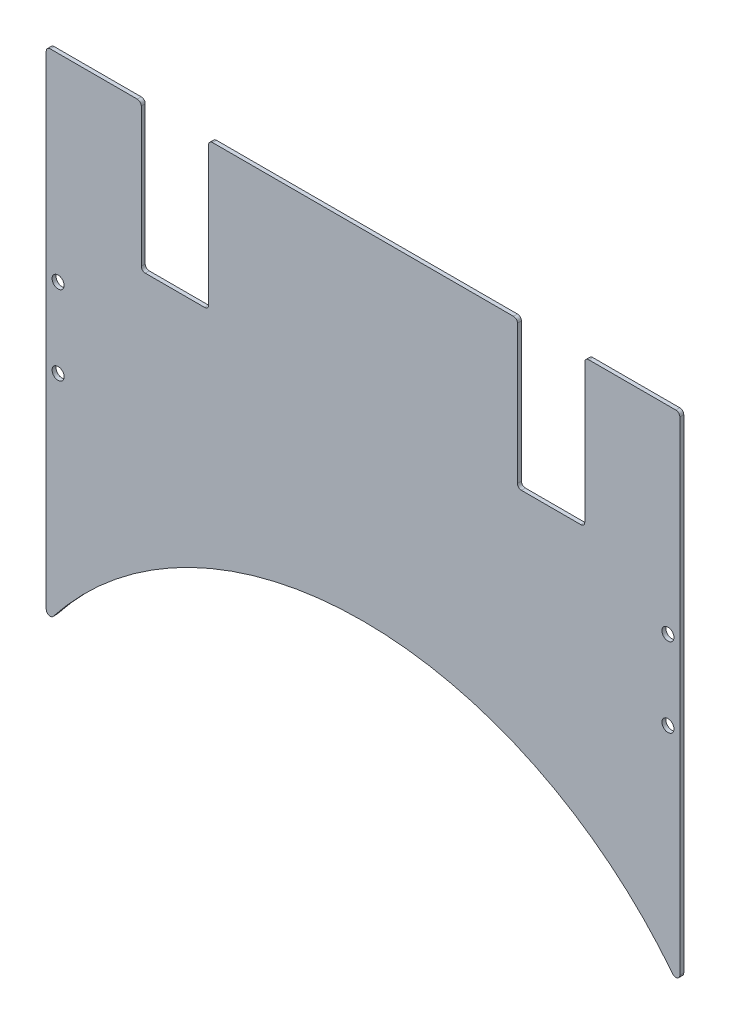
SolidWorks part; units mm, degrees
material "Thornel Mat VMA"
ref_plane "前视基准面" through (0, 0, 0) normal (0, 0, 1) x (1, 0, 0)
ref_plane "上视基准面" through (0, 0, 0) normal (0, 1, 0) x (1, 0, 0)
ref_plane "右视基准面" through (0, 0, 0) normal (1, 0, 0) x (0, 0, -1)
other "Configuration Table"
sketch "草图1" plane through (0, 0, 0) normal (0, 0, 1) x (1, 0, 0)
  line L1 (-80, -52) -> (80, -52)
  line L2 (-80, -52) -> (-80, 52)
  line L3 (-80, 52) -> (80, 52)
  line L4 (80, -52) -> (80, 52)
  line L5 (-80, -52) -> (80, 52) construction
  line L6 (-80, 52) -> (80, -52) construction
  point P0 (0, 0)
  dimension "D1" = 160
  dimension "D2" = 104
extrude "凸台-拉伸1" add sketch "草图1" along normal mid plane 1
sketch "草图2" [suppressed] plane through (0, 0, -0.5) normal (0, 0, -1) x (-1, 0, 0)
  line L0 (-135.1912, -16.9365) -> (135.1912, -16.9365) construction
  line L1 (-135.1912, -16.9365) -> (135.1912, -16.9365) construction
  line L2 (-80, -52) -> (-80, 52) construction
  line L3 (-80, -18.9365) -> (80, -18.9365)
  line L4 (-80, -18.9365) -> (-80, 52)
  line L5 (-80, 52) -> (80, 52)
  line L6 (80, -18.9365) -> (80, 52)
  dimension "D1" = 2
extrude "切除-拉伸1" [suppressed] cut sketch "草图2" against normal mid plane 3
sketch "草图3" [suppressed] plane through (0, 0, -0.5) normal (0, 0, -1) x (-1, 0, 0)
  line L0 (80, 52) -> (80, -52) construction
  line L1 (-80, -52) -> (80, -52)
  line L2 (-80, -52) -> (-80, 12)
  line L3 (-80, 12) -> (80, 12)
  line L4 (80, -52) -> (80, 12)
  line L5 (-80, 52) -> (80, 52) construction
  dimension "D1" = 40
extrude "切除-拉伸2" [suppressed] cut sketch "草图3" against normal mid plane 11
sketch "草图4" [suppressed] plane through (0, 0, -0.5) normal (0, 0, -1) x (-1, 0, 0)
  line L0 (80, 12) -> (-80, 12) construction
  line L1 (-65, 4) -> (65, 4)
  line L2 (-65, 4) -> (-65, 20)
  line L3 (-65, 20) -> (65, 20)
  line L4 (65, 4) -> (65, 20)
  line L5 (-65, 4) -> (65, 20) construction
  line L6 (-65, 20) -> (65, 4) construction
  line L7 (80, 52) -> (80, 12) construction
  point P0 (0, 12)
  dimension "D1" = 8
  dimension "D2" = 15
extrude "切除-拉伸3" [suppressed] cut sketch "草图4" against normal mid plane 11
sketch "草图7" [suppressed] plane through (0, 0, -0.5) normal (0, 0, -1) x (-1, 0, 0)
  line L5 (97.3576, 131.0846) -> (63.5, 131.0846)
  line L6 (63.5, 131.0846) -> (63.5, 72.0846)
  line L7 (63.5, 72.0846) -> (-63.5, 72.0846)
  line L8 (-63.5, 72.0846) -> (-63.5, 82.0846)
  line L9 (-63.5, 82.0846) -> (-83.5434, 82.0846)
  line L10 (97.3576, 131.0846) -> (63.5, 131.0846)
  line L11 (63.5, 131.0846) -> (63.5, 72.0846)
  line L12 (63.5, 72.0846) -> (-63.5, 72.0846)
  line L13 (-63.5, 72.0846) -> (-63.5, 82.0846)
  line L14 (-63.5, 82.0846) -> (-83.5434, 82.0846)
  arc A1 (-83.5434, 82.0846) -> (97.3576, 131.0846) centre (0, 132.0846) ccw
  arc A2 (-83.5434, 82.0846) -> (97.3576, 131.0846) centre (0, 132.0846) ccw
  dimension "D1" = 0
sketch "草图8" [suppressed] plane through (0, 0, -0.5) normal (0, 0, -1) x (-1, 0, 0)
  line L5 (63.5, 133.0846) -> (97.3576, 133.0846)
  line L6 (-92.6256, 162.0846) -> (-63.5, 162.0846)
  line L7 (-63.5, 162.0846) -> (-63.5, 192.0846)
  line L8 (-63.5, 192.0846) -> (63.5, 192.0846)
  line L9 (63.5, 192.0846) -> (63.5, 133.0846)
  line L10 (63.5, 133.0846) -> (97.3576, 133.0846)
  line L11 (-92.6256, 162.0846) -> (-63.5, 162.0846)
  line L12 (-63.5, 162.0846) -> (-63.5, 192.0846)
  line L13 (-63.5, 192.0846) -> (63.5, 192.0846)
  line L14 (63.5, 192.0846) -> (63.5, 133.0846)
  arc A1 (97.3576, 133.0846) -> (-92.6256, 162.0846) centre (0, 132.0846) ccw
  arc A2 (97.3576, 133.0846) -> (-92.6256, 162.0846) centre (0, 132.0846) ccw
  dimension "D1" = 0
sketch "草图9" [suppressed] plane through (0, 0, -0.5) normal (0, 0, -1) x (-1, 0, 0)
  line L5 (-64.5, -134) -> (-96.342, -134)
  line L6 (73.5, -163) -> (64.5, -163)
  line L7 (63.5, -164) -> (63.5, -190)
  line L8 (60.5, -193) -> (-60.5, -193)
  line L17 (-63.5, -190) -> (-63.5, -135)
  line L19 (95.3403, -118) -> (84.5, -118)
  line L21 (83.5, -119) -> (83.5, -153)
  circle A0 centre (0, -133) radius 99.3627
  arc A1 (64.5, -163) -> (63.5, -164) centre (64.5, -164) ccw
  arc A13 (60.5, -193) -> (63.5, -190) centre (60.5, -190) ccw
  arc A15 (-63.5, -190) -> (-60.5, -193) centre (-60.5, -190) ccw
  arc A17 (-63.5, -135) -> (-64.5, -134) centre (-64.5, -135) ccw
  arc A19 (-96.342, -134) -> (-97.3418, -135.0208) centre (-96.342, -135) ccw
  arc A21 (-97.3418, -135.0208) -> (96.3297, -118.8547) centre (0, -133) ccw
  arc A22 (-97.3418, -135.0208) -> (96.3297, -118.8547) centre (0, -133) ccw construction
  arc A23 (96.3297, -118.8547) -> (95.3403, -118) centre (95.3403, -119) ccw
  arc A25 (84.5, -118) -> (83.5, -119) centre (84.5, -119) ccw
  arc A27 (73.5, -163) -> (83.5, -153) centre (73.5, -153) ccw
  dimension "D2" = 2
  dimension "D1" = 0
extrude "切除-拉伸4" [suppressed] cut sketch "草图9" against normal mid plane 31
sketch "草图10" [suppressed] plane through (0, 0, -0.5) normal (0, 0, -1) x (-1, 0, 0)
  line L0 (-80, -52) -> (-80, -74.0682)
  line L1 (-80, -52) -> (-57.5496, -52)
  arc A0 (-57.5496, -52) -> (-80, -74.0682) centre (0, -133) ccw
  arc A1 (57.5496, -52) -> (-57.5496, -52) centre (0, -133) ccw construction
extrude "凸台-拉伸2" [suppressed] add sketch "草图10" against normal up to surface (1 mm away)
mirror "镜向1" [suppressed] about plane through (0, 0, 0) normal (1, 0, 0)
sketch "草图11" [suppressed] plane through (0, 0, -0.5) normal (0, 0, -1) x (-1, 0, 0)
  line L5 (-1, 35.7426) -> (-1, 67.5846)
  line L6 (-2, 68.5846) -> (-57, 68.5846)
  line L7 (-60, 71.5846) -> (-60, 192.5846)
  line L9 (-50, 196.5846) -> (-50, 213.8451)
  line L15 (-57, 195.5846) -> (-51, 195.5846)
  circle A0 centre (0, 132.0846) radius 99.3627
  arc A1 (-51.5293, 214.6935) -> (-2.0208, 34.7428) centre (0, 132.0846) ccw
  arc A10 (-51.5293, 214.6935) -> (-2.0208, 34.7428) centre (0, 132.0846) ccw construction
  arc A11 (-2.0208, 34.7428) -> (-1, 35.7426) centre (-2, 35.7426) ccw
  arc A13 (-1, 67.5846) -> (-2, 68.5846) centre (-2, 67.5846) ccw
  arc A15 (-60, 71.5846) -> (-57, 68.5846) centre (-57, 71.5846) ccw
  arc A17 (-57, 195.5846) -> (-60, 192.5846) centre (-57, 192.5846) ccw
  arc A19 (-51, 195.5846) -> (-50, 196.5846) centre (-51, 196.5846) ccw
  arc A21 (-50, 213.8451) -> (-51.5293, 214.6935) centre (-51, 213.8451) ccw
  dimension "D2" = 2
  dimension "D1" = 0
extrude "切除-拉伸5" [suppressed] cut sketch "草图11" against normal up to surface (1 mm away)
sketch "草图12" plane through (0, 0, -0.5) normal (0, 0, -1) x (-1, 0, 0)
  line L5 (96.342, -134) -> (64.5, -134)
  line L6 (63.5, -135) -> (63.5, -190)
  line L7 (60.5, -193) -> (-60.5, -193)
  line L9 (-64.5, -183) -> (-81.7605, -183)
  line L20 (-63.5, -190) -> (-63.5, -184)
  circle A0 centre (0, -133) radius 99.3627
  arc A1 (-82.609, -184.5293) -> (97.3418, -135.0208) centre (0, -133) ccw
  arc A17 (-82.609, -184.5293) -> (97.3418, -135.0208) centre (0, -133) ccw construction
  arc A18 (97.3418, -135.0208) -> (96.342, -134) centre (96.342, -135) ccw
  arc A20 (64.5, -134) -> (63.5, -135) centre (64.5, -135) ccw
  arc A22 (60.5, -193) -> (63.5, -190) centre (60.5, -190) ccw
  arc A24 (-63.5, -190) -> (-60.5, -193) centre (-60.5, -190) ccw
  arc A26 (-63.5, -184) -> (-64.5, -183) centre (-64.5, -184) ccw
  arc A28 (-81.7605, -183) -> (-82.609, -184.5293) centre (-81.7605, -184) ccw
  dimension "D2" = 2
  dimension "D1" = 0
extrude "切除-拉伸6" cut sketch "草图12" against normal up to surface (1 mm away) up to face at (0, 0, 0.5)
sketch "草图13" plane through (0, 0, -0.5) normal (0, 0, -1) x (-1, 0, 0)
  line L0 (80, -52) -> (80, -74.0682)
  line L1 (80, -52) -> (57.5496, -52)
  arc A0 (80, -74.0682) -> (57.5496, -52) centre (0, -133) ccw
  arc A1 (57.5496, -52) -> (-57.5496, -52) centre (0, -133) ccw construction
extrude "凸台-拉伸3" add sketch "草图13" against normal up to surface (1 mm away) up to face at (0, -14.2729, 0.5)
mirror "镜向2" about plane through (0, 0, 0) normal (1, 0, 0) of "凸台-拉伸3"
sketch "草图14" [suppressed] plane through (0, 0, -0.5) normal (0, 0, -1) x (-1, 0, 0)
  line L5 (1, -196.5846) -> (1, -228.4266)
  line L6 (30, -58.5846) -> (30, -67.5846)
  line L7 (31, -68.5846) -> (57, -68.5846)
  line L8 (60, -71.5846) -> (60, -192.5846)
  line L17 (57, -195.5846) -> (2, -195.5846)
  line L19 (-15, -36.7442) -> (-15, -47.5846)
  line L21 (-14, -48.5846) -> (20, -48.5846)
  circle A0 centre (0, -132.0846) radius 99.3627
  arc A1 (30, -67.5846) -> (31, -68.5846) centre (31, -67.5846) ccw
  arc A13 (60, -71.5846) -> (57, -68.5846) centre (57, -71.5846) ccw
  arc A15 (57, -195.5846) -> (60, -192.5846) centre (57, -192.5846) ccw
  arc A17 (2, -195.5846) -> (1, -196.5846) centre (2, -196.5846) ccw
  arc A19 (1, -228.4266) -> (2.0208, -229.4263) centre (2, -228.4266) ccw
  arc A21 (2.0208, -229.4263) -> (-14.1453, -35.7548) centre (0, -132.0846) ccw
  arc A22 (2.0208, -229.4263) -> (-14.1453, -35.7548) centre (0, -132.0846) ccw construction
  arc A23 (-14.1453, -35.7548) -> (-15, -36.7442) centre (-14, -36.7442) ccw
  arc A25 (-15, -47.5846) -> (-14, -48.5846) centre (-14, -47.5846) ccw
  arc A27 (30, -58.5846) -> (20, -48.5846) centre (20, -58.5846) ccw
  dimension "D2" = 2
  dimension "D1" = 0
extrude "切除-拉伸7" [suppressed] cut sketch "草图14" against normal up to surface (1 mm away)
sketch "草图15" [suppressed] plane through (0, 0, -0.5) normal (0, 0, -1) x (-1, 0, 0)
  line L0 (-53.2393, -34.6238) -> (53.2393, -34.6238)
  line L2 (-53.2393, -34.6238) -> (-53.2393, 13.2547)
  line L3 (-53.2393, 13.2547) -> (53.2393, 13.2547)
  line L4 (-44.0576, -29.6238) -> (44.9575, -29.6238)
  line L5 (46.2393, -28.3422) -> (46.2393, 6.973)
  line L6 (44.9576, 8.2547) -> (-44.0575, 8.2547)
  line L7 (-45.3393, 6.973) -> (-45.3393, -28.3421)
  line L8 (-44.0576, -29.6238) -> (44.9575, -29.6238) construction
  line L9 (46.2393, -28.3422) -> (46.2393, 6.973) construction
  line L10 (44.9576, 8.2547) -> (-44.0575, 8.2547) construction
  line L11 (-45.3393, 6.973) -> (-45.3393, -28.3421) construction
  line L12 (53.2393, -34.6238) -> (53.2393, 13.2547)
  line L13 (-53.2393, -78.6983) -> (53.2393, 13.2547) construction
  line L14 (-53.2393, 13.2547) -> (53.2393, -78.6983) construction
  arc A0 (58.8168, -52) -> (-58.8168, -52) centre (0, -132.0846) ccw construction
  spline S4 degree 2 poles (-566.7757, 2906.9066) (4.2164, -46.3747) (45.447, -29.5283) (45.6842, -29.4314) (45.866, -29.2496) (46.047, -29.0686) (46.1444, -28.8297) (62.928, 12.3297) (-2890.172, 583.6967) knots -43.419559 -43.419559 -43.419559 0.25 0.25 0.5 0.5 0.75 0.75 44.517285 44.517285 44.517285 only from (44.9575, -29.6238) to (46.2393, -28.3422)
  spline S5 degree 2 poles (-2890.2912, -604.7603) (62.9901, -33.7681) (46.1437, 7.4624) (46.0468, 7.6996) (45.865, 7.8814) (45.684, 8.0624) (45.4451, 8.1599) (4.2857, 24.9435) (-567.0812, -2928.1565) knots -43.419559 -43.419559 -43.419559 0.25 0.25 0.5 0.5 0.75 0.75 44.517285 44.517285 44.517285 only from (46.2393, 6.973) to (44.9576, 8.2547)
  spline S6 degree 2 poles (567.6757, -2928.2758) (-3.3164, 25.0055) (-44.547, 8.1592) (-44.7842, 8.0622) (-44.966, 7.8804) (-45.147, 7.6995) (-45.2444, 7.4605) (-62.028, -33.6989) (2891.072, -605.0658) knots -43.419559 -43.419559 -43.419559 0.25 0.25 0.5 0.5 0.75 0.75 44.517285 44.517285 44.517285 only from (-44.0575, 8.2547) to (-45.3393, 6.973)
  spline S7 degree 2 poles (2891.1912, 583.3911) (-62.0901, 12.399) (-45.2437, -28.8315) (-45.1468, -29.0688) (-44.965, -29.2506) (-44.784, -29.4316) (-44.5451, -29.529) (-3.3857, -46.3126) (567.9812, 2906.7874) knots -43.419559 -43.419559 -43.419559 0.25 0.25 0.5 0.5 0.75 0.75 44.517285 44.517285 44.517285 only from (-45.3393, -28.3421) to (-44.0576, -29.6238)
  spline S8 degree 2 poles (44.9575, -29.6238) (45.2109, -29.6247) (45.447, -29.5283) (45.6842, -29.4314) (45.866, -29.2496) (46.047, -29.0686) (46.1444, -28.8297) (46.2403, -28.5946) (46.2393, -28.3422) knots 0 0 0 0.25 0.25 0.5 0.5 0.75 0.75 1 1 1 construction
  spline S9 degree 2 poles (46.2393, 6.973) (46.2402, 7.2264) (46.1437, 7.4624) (46.0468, 7.6996) (45.865, 7.8814) (45.684, 8.0624) (45.4451, 8.1599) (45.21, 8.2557) (44.9576, 8.2547) knots 0 0 0 0.25 0.25 0.5 0.5 0.75 0.75 1 1 1 construction
  spline S10 degree 2 poles (-44.0575, 8.2547) (-44.3109, 8.2556) (-44.547, 8.1592) (-44.7842, 8.0622) (-44.966, 7.8804) (-45.147, 7.6995) (-45.2444, 7.4605) (-45.3403, 7.2254) (-45.3393, 6.973) knots 0 0 0 0.25 0.25 0.5 0.5 0.75 0.75 1 1 1 construction
  spline S11 degree 2 poles (-45.3393, -28.3421) (-45.3402, -28.5955) (-45.2437, -28.8315) (-45.1468, -29.0688) (-44.965, -29.2506) (-44.784, -29.4316) (-44.5451, -29.529) (-44.31, -29.6249) (-44.0576, -29.6238) knots 0 0 0 0.25 0.25 0.5 0.5 0.75 0.75 1 1 1 construction
  point P2 (0, -32.7218)
  dimension "D2" = 5
  dimension "D3" = 7
  dimension "D4" = 98.373
  dimension "D5" = 5
  dimension "D1" = 0
sketch "草图16" [suppressed] plane through (0, 0, -0.5) normal (0, 0, -1) x (-1, 0, 0)
  line L0 (-50, 40.2284) -> (-50, 32.9426) construction
  line L1 (-50, 32.9426) -> (-45, 32.9426) construction
  line L2 (-45, 32.9426) -> (-45, 40.2284) construction
  line L3 (-45, 40.2284) -> (-40, 40.2284) construction
  line L4 (-40, 40.2284) -> (-40, 42.35) construction
  line L5 (-40, 42.35) -> (-55, 42.35) construction
  line L6 (-55, 42.35) -> (-55, 40.2284) construction
  line L7 (-55, 40.2284) -> (-50, 40.2284) construction
  line L8 (-43, 64.0846) -> (-52, 64.0846) construction
  line L9 (-55, 61.0846) -> (-55, 46.55) construction
  line L10 (-55, 46.55) -> (-40, 46.55) construction
  line L11 (-40, 46.55) -> (-40, 61.0846) construction
  line L12 (-50, 40.2284) -> (-50, 32.9426) construction
  line L13 (-50, 32.9426) -> (-45, 32.9426) construction
  line L14 (-45, 32.9426) -> (-45, 40.2284) construction
  line L15 (-45, 40.2284) -> (-40, 40.2284) construction
  line L16 (-40, 40.2284) -> (-40, 42.35) construction
  line L17 (-40, 42.35) -> (-55, 42.35) construction
  line L18 (-55, 42.35) -> (-55, 40.2284) construction
  line L19 (-55, 40.2284) -> (-50, 40.2284) construction
  line L20 (-43, 64.0846) -> (-52, 64.0846) construction
  line L21 (-55, 61.0846) -> (-55, 46.55) construction
  line L22 (-55, 46.55) -> (-40, 46.55) construction
  line L23 (-40, 46.55) -> (-40, 61.0846) construction
  line L24 (-52, 61.0846) -> (-43, 61.0846) construction
  line L26 (-56, 20.9426) -> (-39, 20.9426)
  line L27 (-56, 20.9426) -> (-56, 101.2265)
  line L28 (-56, 101.2265) -> (-39, 101.2265)
  line L29 (-39, 20.9426) -> (-39, 101.2265)
  line L30 (-56, 20.9426) -> (-39, 101.2265) construction
  line L31 (-56, 101.2265) -> (-39, 20.9426) construction
  arc A0 (-52, 64.0846) -> (-55, 61.0846) centre (-52, 61.0846) ccw construction
  arc A1 (-40, 61.0846) -> (-43, 64.0846) centre (-43, 61.0846) ccw construction
  arc A2 (-52, 64.0846) -> (-55, 61.0846) centre (-52, 61.0846) ccw construction
  arc A3 (-40, 61.0846) -> (-43, 64.0846) centre (-43, 61.0846) ccw construction
  point P2 (-47.5, 61.0846)
  dimension "D1" = 1
  dimension "D2" = 18
sketch "草图17" plane through (0, 0, -0.5) normal (0, 0, -1) x (-1, 0, 0)
  line L0 (-50, 40.2284) -> (-50, 32.9426) construction
  line L1 (-50, 32.9426) -> (-45, 32.9426) construction
  line L2 (-45, 32.9426) -> (-45, 40.2284) construction
  line L3 (-45, 40.2284) -> (-40, 40.2284) construction
  line L4 (-40, 40.2284) -> (-40, 42.35) construction
  line L5 (-40, 42.35) -> (-55, 42.35) construction
  line L6 (-55, 42.35) -> (-55, 40.2284) construction
  line L7 (-55, 40.2284) -> (-50, 40.2284) construction
  line L8 (-43, 64.0846) -> (-52, 64.0846) construction
  line L9 (-55, 61.0846) -> (-55, 46.55) construction
  line L10 (-55, 46.55) -> (-40, 46.55) construction
  line L11 (-40, 46.55) -> (-40, 61.0846) construction
  line L12 (-50, 40.2284) -> (-50, 32.9426) construction
  line L13 (-50, 32.9426) -> (-45, 32.9426) construction
  line L14 (-45, 32.9426) -> (-45, 40.2284) construction
  line L15 (-45, 40.2284) -> (-40, 40.2284) construction
  line L16 (-40, 40.2284) -> (-40, 42.35) construction
  line L17 (-40, 42.35) -> (-55, 42.35) construction
  line L18 (-55, 42.35) -> (-55, 40.2284) construction
  line L19 (-55, 40.2284) -> (-50, 40.2284) construction
  line L20 (-43, 64.0846) -> (-52, 64.0846) construction
  line L21 (-55, 61.0846) -> (-55, 46.55) construction
  line L22 (-55, 46.55) -> (-40, 46.55) construction
  line L23 (-40, 46.55) -> (-40, 61.0846) construction
  line L24 (-52, 61.0846) -> (-43, 61.0846) construction
  line L26 (-56, 14.9426) -> (-39, 14.9426)
  line L27 (-56, 14.9426) -> (-56, 107.2265)
  line L28 (-56, 107.2265) -> (-39, 107.2265)
  line L29 (-39, 14.9426) -> (-39, 107.2265)
  line L30 (-56, 14.9426) -> (-39, 107.2265) construction
  line L31 (-56, 107.2265) -> (-39, 14.9426) construction
  arc A0 (-52, 64.0846) -> (-55, 61.0846) centre (-52, 61.0846) ccw construction
  arc A1 (-40, 61.0846) -> (-43, 64.0846) centre (-43, 61.0846) ccw construction
  arc A2 (-52, 64.0846) -> (-55, 61.0846) centre (-52, 61.0846) ccw construction
  arc A3 (-40, 61.0846) -> (-43, 64.0846) centre (-43, 61.0846) ccw construction
  point P2 (-47.5, 61.0846)
  dimension "D1" = 1
  dimension "D2" = 18
extrude "切除-拉伸8" [suppressed] cut sketch "草图16" against normal up to surface (1 mm away)
mirror "镜向3" [suppressed] about plane through (0, 0, 0) normal (1, 0, 0)
extrude "切除-拉伸9" cut sketch "草图17" against normal up to surface (1 mm away) up to face at (0, -0.9264, 0.5)
mirror "镜向4" about plane through (0, 0, 0) normal (1, 0, 0) of "切除-拉伸9"
extrude "切除-拉伸10" [suppressed] cut sketch "草图15" against normal up to surface (1 mm away)
sketch "草图18" [suppressed] plane through (0, 0, -0.5) normal (0, 0, -1) x (-1, 0, 0)
  line L0 (53.2393, 13.2547) -> (-53.2393, 13.2547) construction
  line L1 (-15.75, -4.106) -> (9.25, -4.106)
  line L2 (-15.75, -4.106) -> (-15.75, 30.6154)
  line L3 (-15.75, 30.6154) -> (9.25, 30.6154)
  line L4 (9.25, -4.106) -> (9.25, 30.6154)
  line L5 (-15.75, -4.106) -> (9.25, 30.6154) construction
  line L6 (-15.75, 30.6154) -> (9.25, -4.106) construction
  line L14 (6.25, 17.1154) -> (6.75, 16.6154)
  line L15 (6.75, 16.6154) -> (10.25, 16.6154)
  line L16 (10.25, 16.6154) -> (10.25, 19.3154)
  line L17 (10.25, 19.3154) -> (9.25, 19.3154)
  line L18 (9.25, 19.3154) -> (9.25, 28.5154)
  line L19 (7.25, 30.5154) -> (-13.75, 30.5154)
  line L20 (-15.75, 28.5154) -> (-15.75, 19.3154)
  line L21 (-15.75, 19.3154) -> (-16.75, 19.3154)
  line L22 (-16.75, 19.3154) -> (-16.75, 16.6154)
  line L23 (-16.75, 16.6154) -> (-13.25, 16.6154)
  line L24 (-13.25, 16.6154) -> (-12.75, 17.1154)
  line L25 (-12.75, 17.1154) -> (-12.75, 28.6154)
  line L26 (-12.75, 28.6154) -> (6.25, 28.6154)
  line L27 (6.25, 28.6154) -> (6.25, 17.1154)
  line L28 (6.25, 17.1154) -> (6.75, 16.6154) construction
  line L29 (6.75, 16.6154) -> (10.25, 16.6154) construction
  line L30 (10.25, 16.6154) -> (10.25, 19.3154) construction
  line L31 (10.25, 19.3154) -> (9.25, 19.3154) construction
  line L32 (9.25, 19.3154) -> (9.25, 28.5154) construction
  line L33 (7.25, 30.5154) -> (-13.75, 30.5154) construction
  line L34 (-15.75, 28.5154) -> (-15.75, 19.3154) construction
  line L35 (-15.75, 19.3154) -> (-16.75, 19.3154) construction
  line L36 (-16.75, 19.3154) -> (-16.75, 16.6154) construction
  line L37 (-16.75, 16.6154) -> (-13.25, 16.6154) construction
  line L38 (-13.25, 16.6154) -> (-12.75, 17.1154) construction
  line L39 (-12.75, 17.1154) -> (-12.75, 28.6154) construction
  line L40 (-12.75, 28.6154) -> (6.25, 28.6154) construction
  line L41 (6.25, 28.6154) -> (6.25, 17.1154) construction
  arc A2 (9.25, 28.5154) -> (7.25, 30.5154) centre (7.25, 28.5154) ccw
  arc A3 (-13.75, 30.5154) -> (-15.75, 28.5154) centre (-13.75, 28.5154) ccw
  arc A4 (9.25, 28.5154) -> (7.25, 30.5154) centre (7.25, 28.5154) ccw construction
  arc A5 (-13.75, 30.5154) -> (-15.75, 28.5154) centre (-13.75, 28.5154) ccw construction
  point P6 (-3.25, 13.2547)
  dimension "D2" = 2
  dimension "D3" = 3
  dimension "D4" = 3
  dimension "D1" = 0
extrude "切除-拉伸11" [suppressed] cut sketch "草图18" against normal up to surface (1 mm away)
fillet "圆角1" [suppressed] radius 2
sketch "草图19" [suppressed] plane through (0, 0, -0.5) normal (0, 0, -1) x (-1, 0, 0)
  line L0 (0, 0) -> (0, 34.2033) construction
  circle A0 centre (-77, -18) radius 1.25 construction
  circle A1 centre (-77, 2) radius 1.25 construction
  circle A2 centre (-77, -18) radius 1.25 construction
  circle A3 centre (-77, 2) radius 1.25 construction
  circle A4 centre (-77, 2) radius 1.525
  circle A5 centre (-77, -18) radius 1.525
  circle A6 centre (77, 2) radius 1.25 construction
  circle A7 centre (77, -18) radius 1.25 construction
  circle A8 centre (77, -18) radius 1.525
  circle A9 centre (77, 2) radius 1.525
  dimension "D1" = 3.05
extrude "切除-拉伸12" [suppressed] cut sketch "草图19" against normal blind 40
sketch "草图20" [suppressed] plane through (0, 0, -0.5) normal (0, 0, -1) x (-1, 0, 0)
  line L0 (0, 0) -> (0, 24.9822) construction
  circle A0 centre (-77, -23) radius 1.25 construction
  circle A1 centre (-77, -3) radius 1.25 construction
  circle A2 centre (-77, -23) radius 1.25 construction
  circle A3 centre (-77, -3) radius 1.25 construction
  circle A4 centre (-77, -23) radius 1.525
  circle A5 centre (-77, -3) radius 1.525
  circle A6 centre (77, -3) radius 1.25 construction
  circle A7 centre (77, -23) radius 1.25 construction
  circle A8 centre (77, -3) radius 1.525
  circle A9 centre (77, -23) radius 1.525
  dimension "D1" = 3.05
extrude "切除-拉伸13" [suppressed] cut sketch "草图20" against normal blind 10
sketch "草图21" plane through (0, 0, -0.5) normal (0, 0, -1) x (-1, 0, 0)
  line L0 (0, 0) -> (0, 44.8822) construction
  circle A0 centre (-77, -18) radius 1.25 construction
  circle A1 centre (-77, 2) radius 1.25 construction
  circle A2 centre (-77, -18) radius 1.25 construction
  circle A3 centre (-77, 2) radius 1.25 construction
  circle A4 centre (-77, 2) radius 1.525
  circle A5 centre (-77, -18) radius 1.525
  circle A6 centre (77, 2) radius 1.25 construction
  circle A7 centre (77, -18) radius 1.25 construction
  circle A8 centre (77, -18) radius 1.525
  circle A9 centre (77, 2) radius 1.525
  dimension "D1" = 3.05
extrude "切除-拉伸14" cut sketch "草图21" against normal blind 10
sketch "草图22" [suppressed] plane through (0, 0, 0.5) normal (0, 0, 1) x (1, 0, 0)
  line L0 (0, 0) -> (0, 60.5986) construction
  circle A0 centre (-77, 27) radius 1.25 construction
  circle A1 centre (-77, 47) radius 1.25 construction
  circle A2 centre (-77, 27) radius 1.25 construction
  circle A3 centre (-77, 47) radius 1.25 construction
  circle A4 centre (-77, 27) radius 1.525
  circle A5 centre (-77, 47) radius 1.525
  circle A6 centre (77, 47) radius 1.25 construction
  circle A7 centre (77, 27) radius 1.25 construction
  circle A8 centre (77, 47) radius 1.525
  circle A9 centre (77, 27) radius 1.525
  dimension "D1" = 3.05
extrude "切除-拉伸15" [suppressed] cut sketch "草图22" against normal blind 10
sketch "草图23" [suppressed] plane through (0, 0, -0.5) normal (0, 0, -1) x (-1, 0, 0)
  line L0 (0, 0) -> (0, 60.4735) construction
  circle A0 centre (47.5, 49.1154) radius 1.25 construction
  circle A1 centre (47.5, 41.6154) radius 1.25 construction
  circle A2 centre (47.5, 49.1154) radius 1.25 construction
  circle A3 centre (47.5, 41.6154) radius 1.25 construction
  circle A4 centre (47.5, 49.1154) radius 1.525
  circle A5 centre (47.5, 41.6154) radius 1.525
  circle A6 centre (-47.5, 41.6154) radius 1.25 construction
  circle A7 centre (-47.5, 49.1154) radius 1.25 construction
  circle A8 centre (-47.5, 41.6154) radius 1.525
  circle A9 centre (-47.5, 49.1154) radius 1.525
  dimension "D1" = 3.05
extrude "切除-拉伸16" [suppressed] cut sketch "草图23" against normal blind 10
sketch "草图24" [suppressed] plane through (0, 0, -0.5) normal (0, 0, -1) x (-1, 0, 0)
  line L0 (0, 0) -> (0, -74.6212) construction
  circle A0 centre (47.5, -41.6154) radius 1.25 construction
  circle A1 centre (47.5, -49.1154) radius 1.25 construction
  circle A2 centre (47.5, -41.6154) radius 1.25 construction
  circle A3 centre (47.5, -49.1154) radius 1.25 construction
  circle A4 centre (47.5, -41.6154) radius 1.525
  circle A5 centre (47.5, -49.1154) radius 1.525
  circle A6 centre (-47.5, -49.1154) radius 1.25 construction
  circle A7 centre (-47.5, -41.6154) radius 1.25 construction
  circle A8 centre (-47.5, -49.1154) radius 1.525
  circle A9 centre (-47.5, -41.6154) radius 1.525
  dimension "D1" = 3.05
extrude "切除-拉伸17" [suppressed] cut sketch "草图24" against normal blind 10
fillet "圆角2" [suppressed] radius 1
fillet "圆角3" [suppressed] radius 1
fillet "圆角4" radius 1 12 edges at (-39, 14.9426, 0) (-39, 52, 0) (39, 52, 0) (39, 14.9426, 0) (56, 14.9426, 0) (56, 52, 0) (80, 52, 0) (-80, -74.0682, 0) (80, -74.0682, 0) (-80, 52, 0) (-56, 14.9426, 0) (-56, 52, 0)
fillet "圆角5" [suppressed] radius 1
sketch "草图25" [suppressed] plane through (0, 0, -0.5) normal (0, 0, -1) x (-1, 0, 0)
  circle A0 centre (33.75, -6.8) radius 1.3 construction
  circle A1 centre (22, 49.2) radius 1.3 construction
  circle A2 centre (-22, 49.2) radius 1.3 construction
  circle A3 centre (-33.75, -6.8) radius 1.3 construction
  circle A4 centre (33.75, -6.8) radius 1.3
  circle A5 centre (22, 49.2) radius 1.3
  circle A6 centre (-22, 49.2) radius 1.3
  circle A7 centre (-33.75, -6.8) radius 1.3
extrude "切除-拉伸18" [suppressed] cut sketch "草图25" against normal up to surface (1 mm away)
sketch "草图26" [suppressed] plane through (0, 0, -0.5) normal (0, 0, -1) x (-1, 0, 0)
  line L0 (5, 52) -> (-5, 52) construction
  line L1 (-38, 52) -> (38, 52) construction
  line L2 (5, 47) -> (-5, 47)
  line L3 (5, 57) -> (-5, 57)
  arc A0 (5, 47) -> (5, 57) centre (5, 52) ccw
  arc A1 (-5, 57) -> (-5, 47) centre (-5, 52) ccw
  point P4 (0, 52)
  dimension "D2" = 10
  dimension "D1" = 5
extrude "切除-拉伸20" [suppressed] cut sketch "草图26" against normal up to surface (1 mm away)
fillet "圆角6" [suppressed] radius 1
sketch "草图27" [suppressed] plane through (0, 0, -0.5) normal (0, 0, -1) x (-1, 0, 0)
  line L0 (-76.44, -23.4682) -> (-76.44, -29.4682) construction
  line L1 (-75.44, -23.4682) -> (-75.44, -29.4682)
  line L2 (-77.44, -23.4682) -> (-77.44, -29.4682)
  line L3 (-80, -35.4682) -> (-66.2901, -35.4682) construction
  line L4 (-80, -52) -> (-80, -18.9365) construction
  line L5 (-76.44, -47.4682) -> (-76.44, -41.4682) construction
  line L6 (-75.44, -47.4682) -> (-75.44, -41.4682)
  line L7 (-77.44, -47.4682) -> (-77.44, -41.4682)
  arc A0 (-75.44, -23.4682) -> (-77.44, -23.4682) centre (-76.44, -23.4682) ccw
  arc A1 (-77.44, -29.4682) -> (-75.44, -29.4682) centre (-76.44, -29.4682) ccw
  arc A2 (-75.44, -47.4682) -> (-77.44, -47.4682) centre (-76.44, -47.4682) cw
  arc A3 (-77.44, -41.4682) -> (-75.44, -41.4682) centre (-76.44, -41.4682) cw
  point P2 (-76.44, -26.4682)
  point P13 (-76.44, -44.4682)
  dimension "D1" = 2
  dimension "D2" = 6
  dimension "D3" = 6
  dimension "D4" = 2.56
extrude "切除-拉伸21" [suppressed] cut sketch "草图27" against normal mid plane 10
mirror "镜向5" [suppressed] about plane through (0, 0, 0) normal (1, 0, 0)
fillet "圆角7" [suppressed] radius 2
equation "\"D4@草图18\"=\"D3@草图18\""
